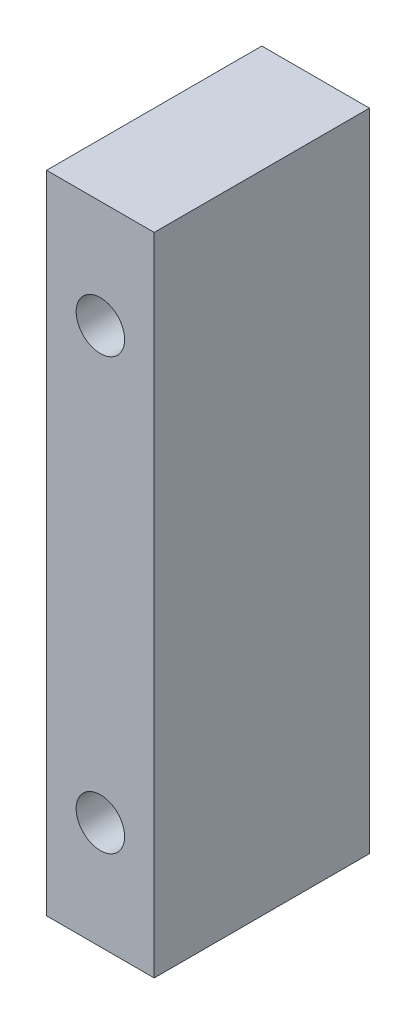
SolidWorks part; units mm, degrees
ref_plane "前视基准面" through (0, 0, 0) normal (0, 0, 1) x (1, 0, 0)
ref_plane "上视基准面" through (0, 0, 0) normal (0, 1, 0) x (1, 0, 0)
ref_plane "右视基准面" through (0, 0, 0) normal (1, 0, 0) x (0, 0, -1)
other "Configuration Table"
sketch "草图1" plane through (0, 0, 0) normal (0, 0, 1) x (1, 0, 0)
  line L1 (0, 0) -> (20, 0)
  line L2 (0, 0) -> (0, 120)
  line L3 (0, 120) -> (20, 120)
  line L4 (20, 0) -> (20, 120)
  circle A0 centre (10, 20) radius 4.5
  circle A1 centre (10, 100) radius 4.5
extrude "Sliding_jaw_20x120x40" add sketch "草图1" along normal blind 40
